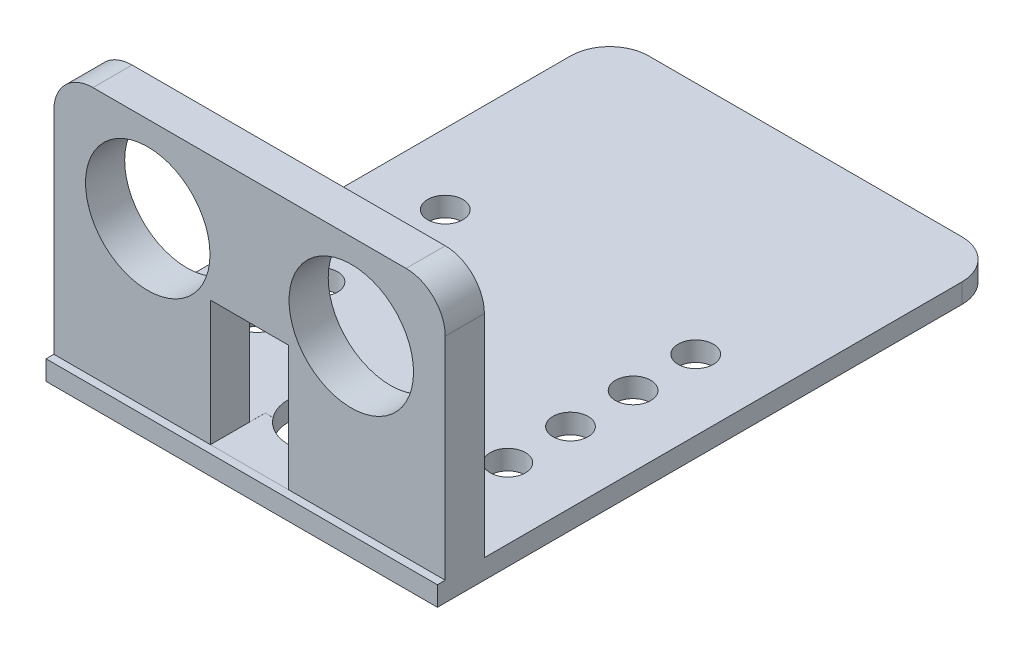
SolidWorks part; units mm, degrees
ref_plane "Front Plane" through (0, 0, 0) normal (0, 0, 1) x (1, 0, 0)
ref_plane "Top Plane" through (0, 0, 0) normal (0, 1, 0) x (1, 0, 0)
ref_plane "Right Plane" through (0, 0, 0) normal (1, 0, 0) x (0, 0, -1)
sketch "Sketch1" plane through (0, 0, 0) normal (0, 1, 0) x (1, 0, 0)
  line L0 (-12, -20) -> (12, -20)
  line L1 (-25, -20) -> (-16, -20)
  line L2 (-25, -20) -> (-25, 20)
  line L3 (-25, 20) -> (25, 20)
  line L4 (25, -20) -> (25, 20)
  line L5 (-25, -20) -> (25, 20) construction
  line L6 (-25, 20) -> (25, -20) construction
  line L8 (-16, -20) -> (-16, -2)
  line L9 (-16, -2) -> (-12, -2)
  line L10 (-12, -20) -> (-12, -2)
  line L12 (12, -20) -> (12, -2)
  line L13 (12, -2) -> (16, -2)
  line L14 (16, -20) -> (16, -2)
  line L15 (16, -20) -> (25, -20)
  circle A0 centre (-16, 16) radius 2.25
  circle A1 centre (-16, 8) radius 2.25
  circle A2 centre (16, 16) radius 2.25
  circle A3 centre (16, 8) radius 2.25
  point P0 (0, 0)
  dimension "D7" = 4.5
  dimension "D8" = 4.5
  dimension "D9" = 4.5
  dimension "D10" = 4.5
  dimension "D1" = 50
  dimension "D2" = 40
  dimension "D3" = 18
  dimension "D4" = 18
  dimension "D5" = 4
  dimension "D6" = 4
  dimension "D11" = 9
  dimension "D12" = 9
  dimension "D13" = 8
  dimension "D14" = 8
  dimension "D15" = 4
  dimension "D16" = 9
  dimension "D17" = 9
  dimension "D18" = 9
  dimension "D19" = 9
  dimension "D20" = 4
extrude "Boss-Extrude1" add sketch "Sketch1" along normal blind 2.5
sketch "Sketch3" plane through (0, 2.5, 0) normal (0, 1, 0) x (1, 0, 0)
  line L0 (-25, -20) -> (-16, -20) construction
  line L1 (-25, 4) -> (25, 4)
  line L2 (-25, 4) -> (-25, -1)
  line L3 (-25, -1) -> (25, -1)
  line L4 (25, 4) -> (25, -1)
  line L12 (25, -20) -> (25, 20)
  line L13 (25, 20) -> (-25, 20)
  line L14 (-25, 20) -> (-25, -20)
  line L15 (-25, -20) -> (-16, -20)
  line L16 (-16, -20) -> (-16, -2)
  line L17 (-16, -2) -> (-12, -2)
  line L18 (-12, -2) -> (-12, -20)
  line L19 (-12, -20) -> (12, -20)
  line L20 (12, -20) -> (12, -2)
  line L21 (12, -2) -> (16, -2)
  line L22 (16, -2) -> (16, -20)
  line L23 (16, -20) -> (25, -20)
  line L24 (25, -20) -> (25, 20)
  line L25 (25, 20) -> (-25, 20)
  line L26 (-25, 20) -> (-25, -20)
  line L27 (-25, -20) -> (-16, -20)
  line L28 (-16, -20) -> (-16, -2)
  line L29 (-16, -2) -> (-12, -2)
  line L30 (-12, -2) -> (-12, -20)
  line L31 (-12, -20) -> (12, -20)
  line L32 (12, -20) -> (12, -2)
  line L33 (12, -2) -> (16, -2)
  line L34 (16, -2) -> (16, -20)
  line L35 (16, -20) -> (25, -20)
  line M17 (25, -20) -> (25, 20)
  line M19 (-25, 20) -> (-25, -20)
  dimension "D2" = 5
  dimension "D3" = 19
  dimension "D1" = 0
extrude "Boss-Extrude2" add sketch "Sketch3" along normal blind 32 contours L3 L1 M19 M17
sketch "Sketch7" plane through (0, 2.5, 0) normal (0, 1, 0) x (1, 0, 0)
  line L0 (25, 20) -> (-25, 20) construction
  circle A0 centre (0, 9) radius 5
  dimension "D2" = 10
  dimension "D1" = 11
extrude "Cut-Extrude3" cut sketch "Sketch7" against normal blind 7 contours A0
sketch "Sketch5" plane through (0, 0, 1) normal (0, 0, 1) x (1, 0, 0)
  line L0 (-5, 18.4943) -> (-5, 2.4943)
  line L1 (-5, 18.4943) -> (5, 18.4943)
  line L2 (-5, 2.4943) -> (5, 2.4943)
  line L3 (5, 18.4943) -> (5, 2.4943)
  line L4 (-5, 18.4943) -> (5, 2.4943) construction
  line L5 (-5, 2.4943) -> (5, 18.4943) construction
  line L6 (-25, 34.5) -> (25, 34.5) construction
  line L7 (0, 2.5) -> (0, 45.5719) construction
  line L8 (-12, 2.5) -> (12, 2.5) construction
  line L9 (0, -11.3336) -> (0, 2.5) construction
  circle A0 centre (-13, 23.5) radius 7.95
  circle A1 centre (13, 23.5) radius 7.95
  point P5 (0, 10.4943)
  dimension "D1" = 15.9
  dimension "D2" = 15.9
  dimension "D3" = 10
  dimension "D4" = 16
  dimension "D5" = 11
  dimension "D6" = 11
  dimension "D7" = 13
  dimension "D8" = 13
extrude "Cut-Extrude1" cut sketch "Sketch5" against normal blind 7
sketch "Sketch4" plane through (0, 0, 0) normal (0, -1, 0) x (1, 0, 0)
  line L1 (-25, 2) -> (25, 2)
  line L2 (-25, 2) -> (-25, -4)
  line L3 (-25, -4) -> (25, -4)
  line L4 (25, 2) -> (25, -4)
  line L12 (25, -20) -> (25, 20)
  line L13 (25, 20) -> (16, 20)
  line L14 (16, 20) -> (16, 2)
  line L15 (16, 2) -> (12, 2)
  line L16 (12, 2) -> (12, 20)
  line L17 (12, 20) -> (-12, 20)
  line L18 (-12, 20) -> (-12, 2)
  line L19 (-12, 2) -> (-16, 2)
  line L20 (-16, 2) -> (-16, 20)
  line L21 (-16, 20) -> (-25, 20)
  line L22 (-25, 20) -> (-25, -20)
  line L23 (-25, -20) -> (25, -20)
  line L24 (25, -20) -> (25, 20)
  line L25 (25, 20) -> (16, 20)
  line L26 (16, 20) -> (16, 2)
  line L27 (16, 2) -> (12, 2)
  line L28 (12, 2) -> (12, 20)
  line L29 (12, 20) -> (-12, 20)
  line L30 (-12, 20) -> (-12, 2)
  line L31 (-12, 2) -> (-16, 2)
  line L32 (-16, 2) -> (-16, 20)
  line L33 (-16, 20) -> (-25, 20)
  line L34 (-25, 20) -> (-25, -20)
  line L35 (-25, -20) -> (25, -20)
  dimension "D2" = 6
  dimension "D3" = 16
  dimension "D1" = 0
sketch "Sketch8" plane through (0, 2.5, 0) normal (0, 1, 0) x (1, 0, 0)
  line L1 (-25, -2) -> (25, -2)
  line L2 (-25, -2) -> (-25, -20)
  line L3 (-25, -20) -> (25, -20)
  line L4 (25, -2) -> (25, -20)
extrude "Cut-Extrude4" cut sketch "Sketch8" against normal through all
sketch "Sketch9" plane through (0, 0, -20) normal (0, 0, -1) x (-1, 0, 0)
  line L1 (-25, 2.5) -> (25, 2.5)
  line L2 (-25, 2.5) -> (-25, 0)
  line L3 (-25, 0) -> (25, 0)
  line L4 (25, 2.5) -> (25, 0)
extrude "Boss-Extrude3" add sketch "Sketch9" along normal blind 50
sketch "Sketch10" plane through (0, 2.5, 0) normal (0, 1, 0) x (1, 0, 0)
  line L0 (0, 0) -> (0, 41.1839) construction
  circle A0 centre (-16, 16) radius 2.25 construction
  circle A1 centre (-16, 16) radius 2.25
  circle A2 centre (-16, 24) radius 2.25
  circle A3 centre (-16, 32) radius 2.25
  circle A4 centre (-16, 40) radius 2.25
  circle A5 centre (16, 40) radius 2.25
  circle A6 centre (16, 32) radius 2.25
  circle A7 centre (16, 24) radius 2.25
  dimension "D1" = 4
extrude "Cut-Extrude5" cut sketch "Sketch10" against normal through all
fillet "Fillet1" radius 5 4 edges at (-25, 34.5, -1.5) (25, 34.5, -1.5) (-25, 1.25, -70) (25, 1.25, -70)
